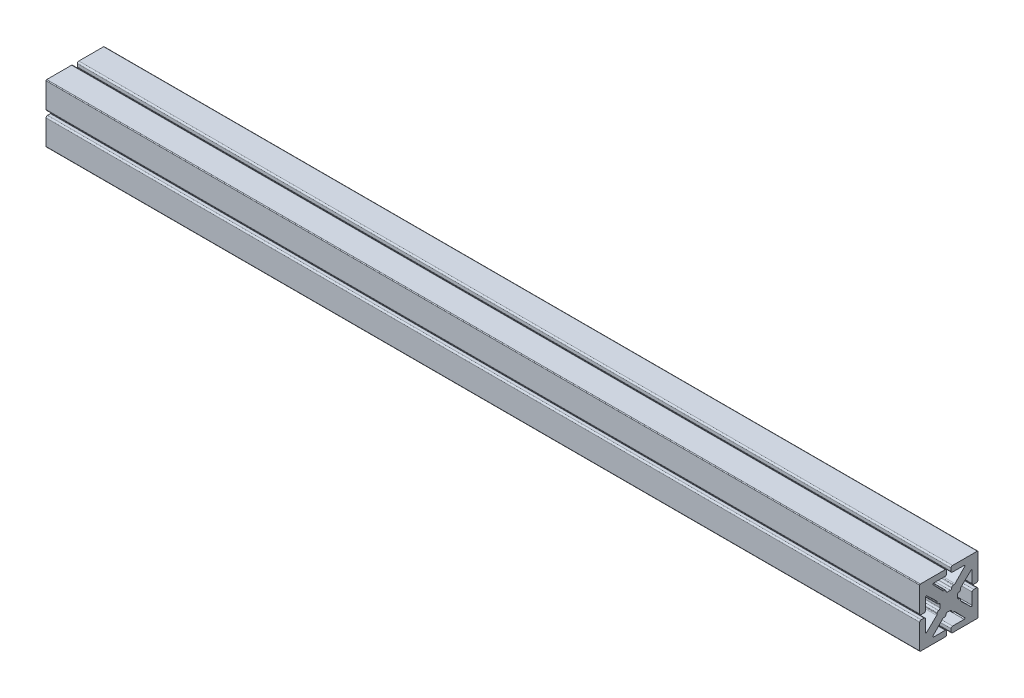
SolidWorks part; units mm, degrees
material "1060 Alloy"
ref_plane "Front Plane" through (0, 0, 0) normal (0, 0, 1) x (1, 0, 0)
ref_plane "Top Plane" through (0, 0, 0) normal (0, 1, 0) x (1, 0, 0)
ref_plane "Right Plane" through (0, 0, 0) normal (1, 0, 0) x (0, 0, -1)
sketch "Sketch1" plane through (0, 0, 0) normal (1, 0, 0) x (0, 0, -1)
  line L0 (0, 0) -> (0, 1.4986) construction
  line L1 (-0.2413, 1.4986) -> (0.2413, 1.4986)
  line L2 (5.0038, 0.635) -> (5.0038, 4.8768)
  line L3 (0.7493, 2.0066) -> (0.8825, 2.0066)
  line L4 (1.0655, 2.0845) -> (2.7141, 3.7982)
  line L5 (2.6226, 4.0132) -> (0.635, 4.0132)
  line L6 (0.381, 4.2672) -> (0.381, 4.7498)
  line L7 (0.635, 5.0038) -> (4.8768, 5.0038)
  line L8 (5.0038, 5.0038) -> (0, 0) construction
  line L9 (0, 0) -> (8.6271, 0) construction
  line L10 (0, 0) -> (0, 5.0038) construction
  line L11 (4.2672, 0.381) -> (4.7498, 0.381)
  line L12 (4.0132, 2.6226) -> (4.0132, 0.635)
  line L13 (2.0845, 1.0655) -> (3.7982, 2.7141)
  line L14 (2.0066, 0.7493) -> (2.0066, 0.8825)
  line L15 (1.4986, -0.2413) -> (1.4986, 0.2413)
  line L16 (0, 0) -> (1.4986, 0) construction
  line L17 (-0.2413, -1.4986) -> (0.2413, -1.4986)
  line L18 (0.7493, -2.0066) -> (0.8825, -2.0066)
  line L19 (1.0655, -2.0845) -> (2.7141, -3.7982)
  line L20 (2.6226, -4.0132) -> (0.635, -4.0132)
  line L21 (0.381, -4.2672) -> (0.381, -4.7498)
  line L22 (0.635, -5.0038) -> (4.8768, -5.0038)
  line L23 (5.0038, -0.635) -> (5.0038, -4.8768)
  line L24 (4.2672, -0.381) -> (4.7498, -0.381)
  line L25 (4.0132, -2.6226) -> (4.0132, -0.635)
  line L26 (2.0845, -1.0655) -> (3.7982, -2.7141)
  line L27 (2.0066, -0.7493) -> (2.0066, -0.8825)
  line L28 (-0.7493, 2.0066) -> (-0.8825, 2.0066)
  line L29 (-1.0655, 2.0845) -> (-2.7141, 3.7982)
  line L30 (-2.6226, 4.0132) -> (-0.635, 4.0132)
  line L31 (-0.381, 4.2672) -> (-0.381, 4.7498)
  line L32 (-0.635, 5.0038) -> (-4.8768, 5.0038)
  line L33 (-5.0038, 0.635) -> (-5.0038, 4.8768)
  line L34 (-4.2672, 0.381) -> (-4.7498, 0.381)
  line L35 (-4.0132, 2.6226) -> (-4.0132, 0.635)
  line L36 (-2.0845, 1.0655) -> (-3.7982, 2.7141)
  line L37 (-2.0066, 0.7493) -> (-2.0066, 0.8825)
  line L38 (-1.4986, -0.2413) -> (-1.4986, 0.2413)
  line L39 (-2.0066, -0.7493) -> (-2.0066, -0.8825)
  line L40 (-2.0845, -1.0655) -> (-3.7982, -2.7141)
  line L41 (-4.0132, -2.6226) -> (-4.0132, -0.635)
  line L42 (-4.2672, -0.381) -> (-4.7498, -0.381)
  line L43 (-5.0038, -0.635) -> (-5.0038, -4.8768)
  line L44 (-0.635, -5.0038) -> (-4.8768, -5.0038)
  line L45 (-0.381, -4.2672) -> (-0.381, -4.7498)
  line L46 (-2.6226, -4.0132) -> (-0.635, -4.0132)
  line L47 (-1.0655, -2.0845) -> (-2.7141, -3.7982)
  line L48 (-0.7493, -2.0066) -> (-0.8825, -2.0066)
  arc A0 (2.7141, 3.7982) -> (2.6226, 4.0132) centre (2.6226, 3.8862) ccw
  arc A1 (0.4953, 1.7526) -> (0.7493, 2.0066) centre (0.7493, 1.7526) cw
  arc A2 (0.8825, 2.0066) -> (1.0655, 2.0845) centre (0.8825, 2.2606) ccw
  arc A3 (0.635, 4.0132) -> (0.381, 4.2672) centre (0.635, 4.2672) cw
  arc A4 (0.381, 4.7498) -> (0.635, 5.0038) centre (0.635, 4.7498) cw
  arc A5 (0.2413, 1.4986) -> (0.4953, 1.7526) centre (0.2413, 1.7526) ccw
  arc A6 (4.7498, 0.381) -> (5.0038, 0.635) centre (4.7498, 0.635) ccw
  arc A7 (4.0132, 0.635) -> (4.2672, 0.381) centre (4.2672, 0.635) ccw
  arc A8 (3.7982, 2.7141) -> (4.0132, 2.6226) centre (3.8862, 2.6226) cw
  arc A9 (2.0066, 0.8825) -> (2.0845, 1.0655) centre (2.2606, 0.8825) cw
  arc A10 (1.7526, 0.4953) -> (2.0066, 0.7493) centre (1.7526, 0.7493) ccw
  arc A11 (1.4986, 0.2413) -> (1.7526, 0.4953) centre (1.7526, 0.2413) cw
  arc A12 (0.2413, -1.4986) -> (0.4953, -1.7526) centre (0.2413, -1.7526) cw
  arc A13 (0.4953, -1.7526) -> (0.7493, -2.0066) centre (0.7493, -1.7526) ccw
  arc A14 (0.8825, -2.0066) -> (1.0655, -2.0845) centre (0.8825, -2.2606) cw
  arc A15 (2.7141, -3.7982) -> (2.6226, -4.0132) centre (2.6226, -3.8862) cw
  arc A16 (0.635, -4.0132) -> (0.381, -4.2672) centre (0.635, -4.2672) ccw
  arc A17 (0.381, -4.7498) -> (0.635, -5.0038) centre (0.635, -4.7498) ccw
  arc A18 (4.7498, -0.381) -> (5.0038, -0.635) centre (4.7498, -0.635) cw
  arc A19 (4.0132, -0.635) -> (4.2672, -0.381) centre (4.2672, -0.635) cw
  arc A20 (3.7982, -2.7141) -> (4.0132, -2.6226) centre (3.8862, -2.6226) ccw
  arc A21 (2.0066, -0.8825) -> (2.0845, -1.0655) centre (2.2606, -0.8825) ccw
  arc A22 (1.7526, -0.4953) -> (2.0066, -0.7493) centre (1.7526, -0.7493) cw
  arc A23 (1.4986, -0.2413) -> (1.7526, -0.4953) centre (1.7526, -0.2413) ccw
  arc A24 (-0.2413, 1.4986) -> (-0.4953, 1.7526) centre (-0.2413, 1.7526) cw
  arc A25 (-0.4953, 1.7526) -> (-0.7493, 2.0066) centre (-0.7493, 1.7526) ccw
  arc A26 (-0.8825, 2.0066) -> (-1.0655, 2.0845) centre (-0.8825, 2.2606) cw
  arc A27 (-2.7141, 3.7982) -> (-2.6226, 4.0132) centre (-2.6226, 3.8862) cw
  arc A28 (-0.635, 4.0132) -> (-0.381, 4.2672) centre (-0.635, 4.2672) ccw
  arc A29 (-0.381, 4.7498) -> (-0.635, 5.0038) centre (-0.635, 4.7498) ccw
  arc A30 (-4.7498, 0.381) -> (-5.0038, 0.635) centre (-4.7498, 0.635) cw
  arc A31 (-4.0132, 0.635) -> (-4.2672, 0.381) centre (-4.2672, 0.635) cw
  arc A32 (-3.7982, 2.7141) -> (-4.0132, 2.6226) centre (-3.8862, 2.6226) ccw
  arc A33 (-2.0066, 0.8825) -> (-2.0845, 1.0655) centre (-2.2606, 0.8825) ccw
  arc A34 (-1.7526, 0.4953) -> (-2.0066, 0.7493) centre (-1.7526, 0.7493) cw
  arc A35 (-1.4986, 0.2413) -> (-1.7526, 0.4953) centre (-1.7526, 0.2413) ccw
  arc A36 (-1.4986, -0.2413) -> (-1.7526, -0.4953) centre (-1.7526, -0.2413) cw
  arc A37 (-1.7526, -0.4953) -> (-2.0066, -0.7493) centre (-1.7526, -0.7493) ccw
  arc A38 (-2.0066, -0.8825) -> (-2.0845, -1.0655) centre (-2.2606, -0.8825) cw
  arc A39 (-3.7982, -2.7141) -> (-4.0132, -2.6226) centre (-3.8862, -2.6226) cw
  arc A40 (-4.0132, -0.635) -> (-4.2672, -0.381) centre (-4.2672, -0.635) ccw
  arc A41 (-4.7498, -0.381) -> (-5.0038, -0.635) centre (-4.7498, -0.635) ccw
  arc A42 (-0.381, -4.7498) -> (-0.635, -5.0038) centre (-0.635, -4.7498) cw
  arc A43 (-0.635, -4.0132) -> (-0.381, -4.2672) centre (-0.635, -4.2672) cw
  arc A44 (-2.7141, -3.7982) -> (-2.6226, -4.0132) centre (-2.6226, -3.8862) ccw
  arc A45 (-0.8825, -2.0066) -> (-1.0655, -2.0845) centre (-0.8825, -2.2606) ccw
  arc A46 (-0.4953, -1.7526) -> (-0.7493, -2.0066) centre (-0.7493, -1.7526) cw
  arc A47 (-0.2413, -1.4986) -> (-0.4953, -1.7526) centre (-0.2413, -1.7526) ccw
  arc A48 (-4.8768, 5.0038) -> (-5.0038, 4.8768) centre (-4.8768, 4.8768) ccw
  arc A49 (-5.0038, -4.8768) -> (-4.8768, -5.0038) centre (-4.8768, -4.8768) ccw
  arc A50 (4.8768, -5.0038) -> (5.0038, -4.8768) centre (4.8768, -4.8768) ccw
  arc A51 (4.8768, 5.0038) -> (5.0038, 4.8768) centre (4.8768, 4.8768) cw
  point P14 (2.921, 4.0132)
  point P19 (0.9906, 2.0066)
  point P150 (0, -1.4986)
  point P152 (-5.0038, 5.0038)
  point P155 (-5.0038, -5.0038)
  point P158 (5.0038, -5.0038)
  dimension "D10" = 0.127
  dimension "D11" = 0.254
  dimension "D2" = 0.127
  dimension "D1" = 10.0076
  dimension "D3" = 2.9972
  dimension "D4" = 0.508
  dimension "D5" = 0.762
  dimension "D6" = 0.9906
  dimension "D7" = 2.54
  dimension "D8" = 1.9812
  dimension "D9" = 0.9906
extrude "Boss-Extrude1" add sketch "Sketch1" along normal blind 2.54 contours L33 A48 L32 A29 L31 A28 L30 A27 L29 A26 L28 A25 A24 L1 A5 A1 L3 A2 L4 A0 L5 A3 L6 A4 L7 A51 L2 A6 L11 A7 L12 A8 L13 A9 L14 A10 A11 L15 A23 A22 L27 A21 L26 A20 L25 A19 L24 A18 L23 A50 L22 A17 L21 A16 L20 A15 L19 A14 L18 A13 A12 L17 A47 A46 L48 A45 L47 A44 L46 A43 L45 A42 L44 A49 L43 A41 L42 A40 L41 A39 L40 A38 L39 A37 A36 L38 A35 A34 L37 A33 L36 A32 L35 A31 L34 A30
scale "Scale1" scale about centroid uniform scaling yes scale factor 8
sketch "Sketch2" plane through (0, 0, 0) normal (1, 0, 0) x (0, 0, -1)
  line L44 (-37.9984, 3.048) -> (-34.1376, 3.048)
  line L45 (-32.1056, 5.08) -> (-32.1056, 20.9808)
  line L46 (-30.3852, 21.7129) -> (-16.676, 8.5244)
  line L47 (-16.0528, 7.06) -> (-16.0528, 5.9944)
  line L48 (-11.9888, 1.9304) -> (-11.9888, -1.9304)
  line L49 (-16.0528, -5.9944) -> (-16.0528, -7.06)
  line L50 (-16.676, -8.5244) -> (-30.3852, -21.7129)
  line L51 (-32.1056, -20.9808) -> (-32.1056, -5.08)
  line L52 (-34.1376, -3.048) -> (-37.9984, -3.048)
  line L53 (-40.0304, -5.08) -> (-40.0304, -39.0144)
  line L54 (-39.0144, -40.0304) -> (-5.08, -40.0304)
  line L55 (-3.048, -37.9984) -> (-3.048, -34.1376)
  line L56 (-5.08, -32.1056) -> (-20.9808, -32.1056)
  line L57 (-21.7129, -30.3852) -> (-8.5244, -16.676)
  line L58 (-7.06, -16.0528) -> (-5.9944, -16.0528)
  line L59 (-1.9304, -11.9888) -> (1.9304, -11.9888)
  line L60 (5.9944, -16.0528) -> (7.06, -16.0528)
  line L61 (8.5244, -16.676) -> (21.7129, -30.3852)
  line L62 (20.9808, -32.1056) -> (5.08, -32.1056)
  line L63 (3.048, -34.1376) -> (3.048, -37.9984)
  line L64 (5.08, -40.0304) -> (39.0144, -40.0304)
  line L65 (40.0304, -39.0144) -> (40.0304, -5.08)
  line L66 (37.9984, -3.048) -> (34.1376, -3.048)
  line L67 (32.1056, -5.08) -> (32.1056, -20.9808)
  line L68 (30.3852, -21.7129) -> (16.676, -8.5244)
  line L69 (16.0528, -7.06) -> (16.0528, -5.9944)
  line L70 (11.9888, -1.9304) -> (11.9888, 1.9304)
  line L71 (16.0528, 5.9944) -> (16.0528, 7.06)
  line L72 (16.676, 8.5244) -> (30.3852, 21.7129)
  line L73 (32.1056, 20.9808) -> (32.1056, 5.08)
  line L74 (34.1376, 3.048) -> (37.9984, 3.048)
  line L75 (40.0304, 5.08) -> (40.0304, 39.0144)
  line L76 (39.0144, 40.0304) -> (5.08, 40.0304)
  line L77 (3.048, 37.9984) -> (3.048, 34.1376)
  line L78 (5.08, 32.1056) -> (20.9808, 32.1056)
  line L79 (21.7129, 30.3852) -> (8.5244, 16.676)
  line L80 (7.06, 16.0528) -> (5.9944, 16.0528)
  line L81 (1.9304, 11.9888) -> (-1.9304, 11.9888)
  line L82 (-5.9944, 16.0528) -> (-7.06, 16.0528)
  line L83 (-8.5244, 16.676) -> (-21.7129, 30.3852)
  line L84 (-20.9808, 32.1056) -> (-5.08, 32.1056)
  line L85 (-3.048, 34.1376) -> (-3.048, 37.9984)
  line L86 (-5.08, 40.0304) -> (-39.0144, 40.0304)
  line L87 (-40.0304, 39.0144) -> (-40.0304, 5.08)
  line L88 (-37.9984, 3.048) -> (-34.1376, 3.048)
  line L89 (-32.1056, 5.08) -> (-32.1056, 20.9808)
  line L90 (-30.3852, 21.7129) -> (-16.676, 8.5244)
  line L91 (-16.0528, 7.06) -> (-16.0528, 5.9944)
  line L92 (-11.9888, 1.9304) -> (-11.9888, -1.9304)
  line L93 (-16.0528, -5.9944) -> (-16.0528, -7.06)
  line L94 (-16.676, -8.5244) -> (-30.3852, -21.7129)
  line L95 (-32.1056, -20.9808) -> (-32.1056, -5.08)
  line L96 (-34.1376, -3.048) -> (-37.9984, -3.048)
  line L97 (-40.0304, -5.08) -> (-40.0304, -39.0144)
  line L98 (-39.0144, -40.0304) -> (-5.08, -40.0304)
  line L99 (-3.048, -37.9984) -> (-3.048, -34.1376)
  line L100 (-5.08, -32.1056) -> (-20.9808, -32.1056)
  line L101 (-21.7129, -30.3852) -> (-8.5244, -16.676)
  line L102 (-7.06, -16.0528) -> (-5.9944, -16.0528)
  line L103 (-1.9304, -11.9888) -> (1.9304, -11.9888)
  line L104 (5.9944, -16.0528) -> (7.06, -16.0528)
  line L105 (8.5244, -16.676) -> (21.7129, -30.3852)
  line L106 (20.9808, -32.1056) -> (5.08, -32.1056)
  line L107 (3.048, -34.1376) -> (3.048, -37.9984)
  line L108 (5.08, -40.0304) -> (39.0144, -40.0304)
  line L109 (40.0304, -39.0144) -> (40.0304, -5.08)
  line L110 (37.9984, -3.048) -> (34.1376, -3.048)
  line L111 (32.1056, -5.08) -> (32.1056, -20.9808)
  line L112 (30.3852, -21.7129) -> (16.676, -8.5244)
  line L113 (16.0528, -7.06) -> (16.0528, -5.9944)
  line L114 (11.9888, -1.9304) -> (11.9888, 1.9304)
  line L115 (16.0528, 5.9944) -> (16.0528, 7.06)
  line L116 (16.676, 8.5244) -> (30.3852, 21.7129)
  line L117 (32.1056, 20.9808) -> (32.1056, 5.08)
  line L118 (34.1376, 3.048) -> (37.9984, 3.048)
  line L119 (40.0304, 5.08) -> (40.0304, 39.0144)
  line L120 (39.0144, 40.0304) -> (5.08, 40.0304)
  line L121 (3.048, 37.9984) -> (3.048, 34.1376)
  line L122 (5.08, 32.1056) -> (20.9808, 32.1056)
  line L123 (21.7129, 30.3852) -> (8.5244, 16.676)
  line L124 (7.06, 16.0528) -> (5.9944, 16.0528)
  line L125 (1.9304, 11.9888) -> (-1.9304, 11.9888)
  line L126 (-5.9944, 16.0528) -> (-7.06, 16.0528)
  line L127 (-8.5244, 16.676) -> (-21.7129, 30.3852)
  line L128 (-20.9808, 32.1056) -> (-5.08, 32.1056)
  line L129 (-3.048, 34.1376) -> (-3.048, 37.9984)
  line L130 (-5.08, 40.0304) -> (-39.0144, 40.0304)
  line L131 (-40.0304, 39.0144) -> (-40.0304, 5.08)
  arc A52 (-40.0304, 5.08) -> (-37.9984, 3.048) centre (-37.9984, 5.08) ccw
  arc A53 (-34.1376, 3.048) -> (-32.1056, 5.08) centre (-34.1376, 5.08) ccw
  arc A54 (-30.3852, 21.7129) -> (-32.1056, 20.9808) centre (-31.0896, 20.9808) ccw
  arc A55 (-16.0528, 7.06) -> (-16.676, 8.5244) centre (-18.0848, 7.06) ccw
  arc A56 (-16.0528, 5.9944) -> (-14.0208, 3.9624) centre (-14.0208, 5.9944) ccw
  arc A57 (-11.9888, 1.9304) -> (-14.0208, 3.9624) centre (-14.0208, 1.9304) ccw
  arc A58 (-14.0208, -3.9624) -> (-11.9888, -1.9304) centre (-14.0208, -1.9304) ccw
  arc A59 (-14.0208, -3.9624) -> (-16.0528, -5.9944) centre (-14.0208, -5.9944) ccw
  arc A60 (-16.676, -8.5244) -> (-16.0528, -7.06) centre (-18.0848, -7.06) ccw
  arc A61 (-32.1056, -20.9808) -> (-30.3852, -21.7129) centre (-31.0896, -20.9808) ccw
  arc A62 (-32.1056, -5.08) -> (-34.1376, -3.048) centre (-34.1376, -5.08) ccw
  arc A63 (-37.9984, -3.048) -> (-40.0304, -5.08) centre (-37.9984, -5.08) ccw
  arc A64 (-40.0304, -39.0144) -> (-39.0144, -40.0304) centre (-39.0144, -39.0144) ccw
  arc A65 (-5.08, -40.0304) -> (-3.048, -37.9984) centre (-5.08, -37.9984) ccw
  arc A66 (-3.048, -34.1376) -> (-5.08, -32.1056) centre (-5.08, -34.1376) ccw
  arc A67 (-21.7129, -30.3852) -> (-20.9808, -32.1056) centre (-20.9808, -31.0896) ccw
  arc A68 (-7.06, -16.0528) -> (-8.5244, -16.676) centre (-7.06, -18.0848) ccw
  arc A69 (-5.9944, -16.0528) -> (-3.9624, -14.0208) centre (-5.9944, -14.0208) ccw
  arc A70 (-1.9304, -11.9888) -> (-3.9624, -14.0208) centre (-1.9304, -14.0208) ccw
  arc A71 (3.9624, -14.0208) -> (1.9304, -11.9888) centre (1.9304, -14.0208) ccw
  arc A72 (3.9624, -14.0208) -> (5.9944, -16.0528) centre (5.9944, -14.0208) ccw
  arc A73 (8.5244, -16.676) -> (7.06, -16.0528) centre (7.06, -18.0848) ccw
  arc A74 (20.9808, -32.1056) -> (21.7129, -30.3852) centre (20.9808, -31.0896) ccw
  arc A75 (5.08, -32.1056) -> (3.048, -34.1376) centre (5.08, -34.1376) ccw
  arc A76 (3.048, -37.9984) -> (5.08, -40.0304) centre (5.08, -37.9984) ccw
  arc A77 (39.0144, -40.0304) -> (40.0304, -39.0144) centre (39.0144, -39.0144) ccw
  arc A78 (40.0304, -5.08) -> (37.9984, -3.048) centre (37.9984, -5.08) ccw
  arc A79 (34.1376, -3.048) -> (32.1056, -5.08) centre (34.1376, -5.08) ccw
  arc A80 (30.3852, -21.7129) -> (32.1056, -20.9808) centre (31.0896, -20.9808) ccw
  arc A81 (16.0528, -7.06) -> (16.676, -8.5244) centre (18.0848, -7.06) ccw
  arc A82 (16.0528, -5.9944) -> (14.0208, -3.9624) centre (14.0208, -5.9944) ccw
  arc A83 (11.9888, -1.9304) -> (14.0208, -3.9624) centre (14.0208, -1.9304) ccw
  arc A84 (14.0208, 3.9624) -> (11.9888, 1.9304) centre (14.0208, 1.9304) ccw
  arc A85 (14.0208, 3.9624) -> (16.0528, 5.9944) centre (14.0208, 5.9944) ccw
  arc A86 (16.676, 8.5244) -> (16.0528, 7.06) centre (18.0848, 7.06) ccw
  arc A87 (32.1056, 20.9808) -> (30.3852, 21.7129) centre (31.0896, 20.9808) ccw
  arc A88 (32.1056, 5.08) -> (34.1376, 3.048) centre (34.1376, 5.08) ccw
  arc A89 (37.9984, 3.048) -> (40.0304, 5.08) centre (37.9984, 5.08) ccw
  arc A90 (40.0304, 39.0144) -> (39.0144, 40.0304) centre (39.0144, 39.0144) ccw
  arc A91 (5.08, 40.0304) -> (3.048, 37.9984) centre (5.08, 37.9984) ccw
  arc A92 (3.048, 34.1376) -> (5.08, 32.1056) centre (5.08, 34.1376) ccw
  arc A93 (21.7129, 30.3852) -> (20.9808, 32.1056) centre (20.9808, 31.0896) ccw
  arc A94 (7.06, 16.0528) -> (8.5244, 16.676) centre (7.06, 18.0848) ccw
  arc A95 (5.9944, 16.0528) -> (3.9624, 14.0208) centre (5.9944, 14.0208) ccw
  arc A96 (1.9304, 11.9888) -> (3.9624, 14.0208) centre (1.9304, 14.0208) ccw
  arc A97 (-3.9624, 14.0208) -> (-1.9304, 11.9888) centre (-1.9304, 14.0208) ccw
  arc A98 (-3.9624, 14.0208) -> (-5.9944, 16.0528) centre (-5.9944, 14.0208) ccw
  arc A99 (-8.5244, 16.676) -> (-7.06, 16.0528) centre (-7.06, 18.0848) ccw
  arc A100 (-20.9808, 32.1056) -> (-21.7129, 30.3852) centre (-20.9808, 31.0896) ccw
  arc A101 (-5.08, 32.1056) -> (-3.048, 34.1376) centre (-5.08, 34.1376) ccw
  arc A102 (-3.048, 37.9984) -> (-5.08, 40.0304) centre (-5.08, 37.9984) ccw
  arc A103 (-39.0144, 40.0304) -> (-40.0304, 39.0144) centre (-39.0144, 39.0144) ccw
  arc A104 (-40.0304, 5.08) -> (-37.9984, 3.048) centre (-37.9984, 5.08) ccw
  arc A105 (-34.1376, 3.048) -> (-32.1056, 5.08) centre (-34.1376, 5.08) ccw
  arc A106 (-30.3852, 21.7129) -> (-32.1056, 20.9808) centre (-31.0896, 20.9808) ccw
  arc A107 (-16.0528, 7.06) -> (-16.676, 8.5244) centre (-18.0848, 7.06) ccw
  arc A108 (-16.0528, 5.9944) -> (-14.0208, 3.9624) centre (-14.0208, 5.9944) ccw
  arc A109 (-11.9888, 1.9304) -> (-14.0208, 3.9624) centre (-14.0208, 1.9304) ccw
  arc A110 (-14.0208, -3.9624) -> (-11.9888, -1.9304) centre (-14.0208, -1.9304) ccw
  arc A111 (-14.0208, -3.9624) -> (-16.0528, -5.9944) centre (-14.0208, -5.9944) ccw
  arc A112 (-16.676, -8.5244) -> (-16.0528, -7.06) centre (-18.0848, -7.06) ccw
  arc A113 (-32.1056, -20.9808) -> (-30.3852, -21.7129) centre (-31.0896, -20.9808) ccw
  arc A114 (-32.1056, -5.08) -> (-34.1376, -3.048) centre (-34.1376, -5.08) ccw
  arc A115 (-37.9984, -3.048) -> (-40.0304, -5.08) centre (-37.9984, -5.08) ccw
  arc A116 (-40.0304, -39.0144) -> (-39.0144, -40.0304) centre (-39.0144, -39.0144) ccw
  arc A117 (-5.08, -40.0304) -> (-3.048, -37.9984) centre (-5.08, -37.9984) ccw
  arc A118 (-3.048, -34.1376) -> (-5.08, -32.1056) centre (-5.08, -34.1376) ccw
  arc A119 (-21.7129, -30.3852) -> (-20.9808, -32.1056) centre (-20.9808, -31.0896) ccw
  arc A120 (-7.06, -16.0528) -> (-8.5244, -16.676) centre (-7.06, -18.0848) ccw
  arc A121 (-5.9944, -16.0528) -> (-3.9624, -14.0208) centre (-5.9944, -14.0208) ccw
  arc A122 (-1.9304, -11.9888) -> (-3.9624, -14.0208) centre (-1.9304, -14.0208) ccw
  arc A123 (3.9624, -14.0208) -> (1.9304, -11.9888) centre (1.9304, -14.0208) ccw
  arc A124 (3.9624, -14.0208) -> (5.9944, -16.0528) centre (5.9944, -14.0208) ccw
  arc A125 (8.5244, -16.676) -> (7.06, -16.0528) centre (7.06, -18.0848) ccw
  arc A126 (20.9808, -32.1056) -> (21.7129, -30.3852) centre (20.9808, -31.0896) ccw
  arc A127 (5.08, -32.1056) -> (3.048, -34.1376) centre (5.08, -34.1376) ccw
  arc A128 (3.048, -37.9984) -> (5.08, -40.0304) centre (5.08, -37.9984) ccw
  arc A129 (39.0144, -40.0304) -> (40.0304, -39.0144) centre (39.0144, -39.0144) ccw
  arc A130 (40.0304, -5.08) -> (37.9984, -3.048) centre (37.9984, -5.08) ccw
  arc A131 (34.1376, -3.048) -> (32.1056, -5.08) centre (34.1376, -5.08) ccw
  arc A132 (30.3852, -21.7129) -> (32.1056, -20.9808) centre (31.0896, -20.9808) ccw
  arc A133 (16.0528, -7.06) -> (16.676, -8.5244) centre (18.0848, -7.06) ccw
  arc A134 (16.0528, -5.9944) -> (14.0208, -3.9624) centre (14.0208, -5.9944) ccw
  arc A135 (11.9888, -1.9304) -> (14.0208, -3.9624) centre (14.0208, -1.9304) ccw
  arc A136 (14.0208, 3.9624) -> (11.9888, 1.9304) centre (14.0208, 1.9304) ccw
  arc A137 (14.0208, 3.9624) -> (16.0528, 5.9944) centre (14.0208, 5.9944) ccw
  arc A138 (16.676, 8.5244) -> (16.0528, 7.06) centre (18.0848, 7.06) ccw
  arc A139 (32.1056, 20.9808) -> (30.3852, 21.7129) centre (31.0896, 20.9808) ccw
  arc A140 (32.1056, 5.08) -> (34.1376, 3.048) centre (34.1376, 5.08) ccw
  arc A141 (37.9984, 3.048) -> (40.0304, 5.08) centre (37.9984, 5.08) ccw
  arc A142 (40.0304, 39.0144) -> (39.0144, 40.0304) centre (39.0144, 39.0144) ccw
  arc A143 (5.08, 40.0304) -> (3.048, 37.9984) centre (5.08, 37.9984) ccw
  arc A144 (3.048, 34.1376) -> (5.08, 32.1056) centre (5.08, 34.1376) ccw
  arc A145 (21.7129, 30.3852) -> (20.9808, 32.1056) centre (20.9808, 31.0896) ccw
  arc A146 (7.06, 16.0528) -> (8.5244, 16.676) centre (7.06, 18.0848) ccw
  arc A147 (5.9944, 16.0528) -> (3.9624, 14.0208) centre (5.9944, 14.0208) ccw
  arc A148 (1.9304, 11.9888) -> (3.9624, 14.0208) centre (1.9304, 14.0208) ccw
  arc A149 (-3.9624, 14.0208) -> (-1.9304, 11.9888) centre (-1.9304, 14.0208) ccw
  arc A150 (-3.9624, 14.0208) -> (-5.9944, 16.0528) centre (-5.9944, 14.0208) ccw
  arc A151 (-8.5244, 16.676) -> (-7.06, 16.0528) centre (-7.06, 18.0848) ccw
  arc A152 (-20.9808, 32.1056) -> (-21.7129, 30.3852) centre (-20.9808, 31.0896) ccw
  arc A153 (-5.08, 32.1056) -> (-3.048, 34.1376) centre (-5.08, 34.1376) ccw
  arc A154 (-3.048, 37.9984) -> (-5.08, 40.0304) centre (-5.08, 37.9984) ccw
  arc A155 (-39.0144, 40.0304) -> (-40.0304, 39.0144) centre (-39.0144, 39.0144) ccw
  dimension "D1" = 0
extrude "Boss-Extrude2" add sketch "Sketch2" along normal mid plane 1200
ref_point "Point1"
ref_point "Point2"
